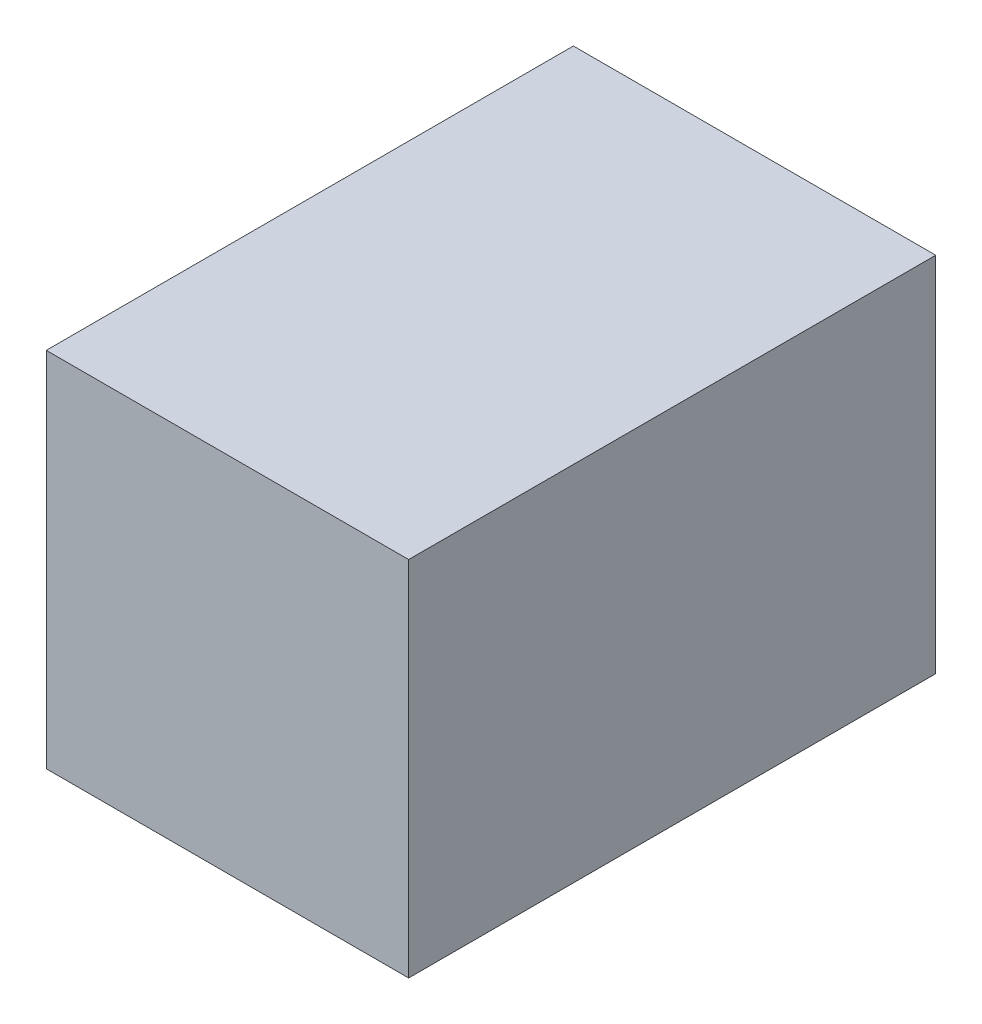
SolidWorks part; units mm, degrees
material "PLA"
ref_plane "Front Plane" through (0, 0, 0) normal (1, 0, 0) x (0, 1, 0)
ref_plane "Top Plane" through (0, 0, 0) normal (0, 0, 1) x (0, 1, 0)
ref_plane "Right Plane" through (0, 0, 0) normal (0, 1, 0) x (-1, 0, 0)
sketch "Sketch1" plane through (0, 0, 0) normal (0, 0, 1) x (0, 1, 0)
  line L1 (-13.75, -13.75) -> (13.75, -13.75)
  line L2 (-13.75, -13.75) -> (-13.75, 13.75)
  line L3 (-13.75, 13.75) -> (13.75, 13.75)
  line L4 (13.75, -13.75) -> (13.75, 13.75)
  line L5 (-13.75, -13.75) -> (13.75, 13.75) construction
  line L6 (-13.75, 13.75) -> (13.75, -13.75) construction
  point P0 (0, 0)
  dimension "D2" = 27.5
extrude "Boss-Extrude1" add sketch "Sketch1" along normal blind 40
equation "\"ball_diameter\"= 0.75in"
equation "\"wall_thickness\" = 0.25cm"
equation "\"track_length\" = 25cm"
equation "\"axle\" = 5mm"
equation "\"pillar_width\" = 2.75cm"
equation "\"D2@Sketch1\"=\"pillar_width\""
